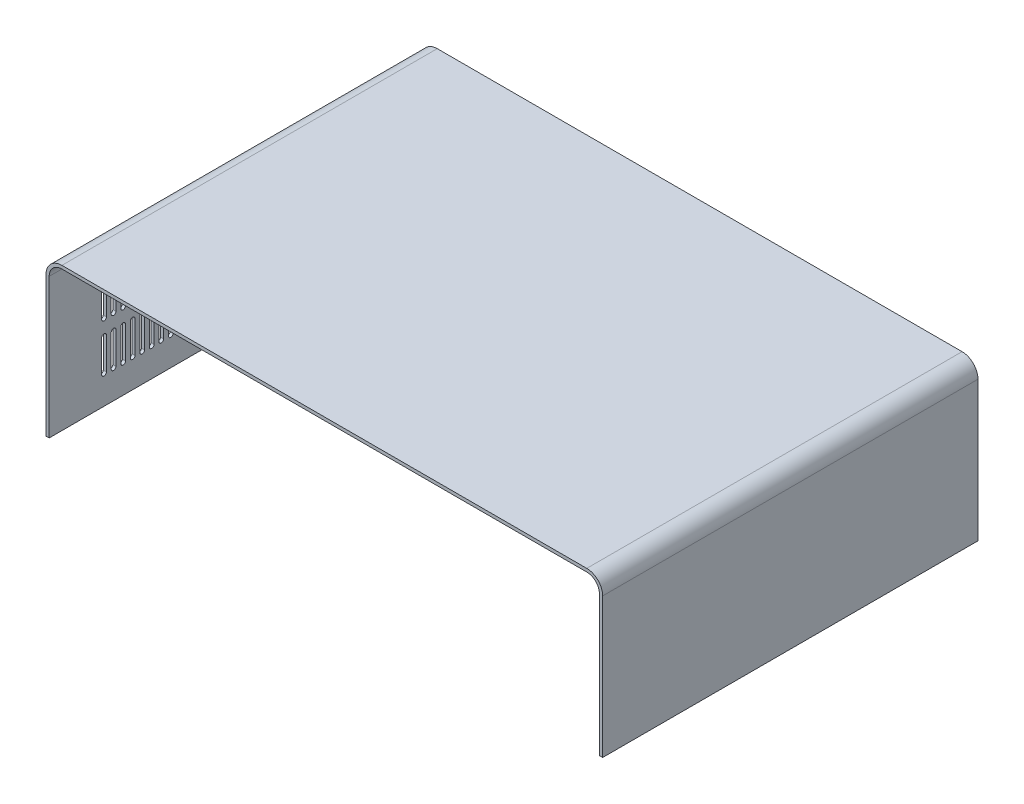
SolidWorks part; units mm, degrees
ref_plane "Front Plane" through (0, 0, 0) normal (0, 0, 1) x (1, 0, 0)
ref_plane "Top Plane" through (0, 0, 0) normal (0, 1, 0) x (1, 0, 0)
ref_plane "Right Plane" through (0, 0, 0) normal (1, 0, 0) x (0, 0, -1)
sketch "Sketch1" plane through (0, 0, 0) normal (0, 0, 1) x (1, 0, 0)
  line L0 (-87.5, 0) -> (-87.5, 44)
  line L1 (-82.5, 49) -> (82.5, 49)
  line L2 (87.5, 44) -> (87.5, 0)
  line L3 (-86.5, 0) -> (-86.5, 44)
  line L4 (-82.5, 48) -> (82.5, 48)
  line L5 (86.5, 44) -> (86.5, 0)
  line L6 (-87.5, 0) -> (-86.5, 0)
  line L7 (86.5, 0) -> (87.5, 0)
  arc A0 (-87.5, 44) -> (-82.5, 49) centre (-82.5, 44) cw
  arc A1 (82.5, 49) -> (87.5, 44) centre (82.5, 44) cw
  arc A2 (-86.5, 44) -> (-82.5, 48) centre (-82.5, 44) cw
  arc A3 (82.5, 48) -> (86.5, 44) centre (82.5, 44) cw
  point P16 (0, 49)
  dimension "D1" = 5
  dimension "D2" = 5
  dimension "D3" = 49
  dimension "D4" = 175
  dimension "D5" = 1
extrude "Extrude1" add sketch "Sketch1" against normal blind 118
sketch "Sketch2" plane through (-87.5, 0, 0) normal (-1, 0, 0) x (0, 0, 1)
  line L0 (-75, 34) -> (-75, 24)
  line L1 (-73.5, 34) -> (-73.5, 24)
  line L2 (0, 44) -> (0, 0) construction
  line L3 (-118, 49) -> (0, 49) construction
  line L4 (-72, 34) -> (-72, 24)
  line L5 (-70.5, 34) -> (-70.5, 24)
  line L6 (-69, 34) -> (-69, 24)
  line L7 (-67.5, 34) -> (-67.5, 24)
  line L8 (-66, 34) -> (-66, 24)
  line L9 (-64.5, 34) -> (-64.5, 24)
  line L10 (-63, 34) -> (-63, 24)
  line L11 (-61.5, 34) -> (-61.5, 24)
  line L12 (-60, 34) -> (-60, 24)
  line L13 (-58.5, 34) -> (-58.5, 24)
  line L14 (-57, 34) -> (-57, 24)
  line L15 (-55.5, 34) -> (-55.5, 24)
  line L16 (-54, 34) -> (-54, 24)
  line L17 (-52.5, 34) -> (-52.5, 24)
  line L18 (-51, 34) -> (-51, 24)
  line L19 (-49.5, 34) -> (-49.5, 24)
  line L20 (-48, 34) -> (-48, 24)
  line L21 (-46.5, 34) -> (-46.5, 24)
  line L22 (-45, 34) -> (-45, 24)
  line L23 (-43.5, 34) -> (-43.5, 24)
  line L24 (-42, 34) -> (-42, 24)
  line L25 (-40.5, 34) -> (-40.5, 24)
  line L26 (-39, 34) -> (-39, 24)
  line L27 (-37.5, 34) -> (-37.5, 24)
  line L28 (-36, 34) -> (-36, 24)
  line L29 (-34.5, 34) -> (-34.5, 24)
  line L30 (-33, 34) -> (-33, 24)
  line L31 (-31.5, 34) -> (-31.5, 24)
  line L32 (-30, 34) -> (-30, 24)
  line L33 (-28.5, 34) -> (-28.5, 24)
  line L34 (-27, 34) -> (-27, 24)
  line L35 (-25.5, 34) -> (-25.5, 24)
  line L36 (-24, 34) -> (-24, 24)
  line L37 (-22.5, 34) -> (-22.5, 24)
  line L38 (-21, 34) -> (-21, 24)
  line L39 (-19.5, 34) -> (-19.5, 24)
  line L40 (-18, 34) -> (-18, 24)
  line L41 (-16.5, 34) -> (-16.5, 24)
  line L42 (-75, 19) -> (-75, 9)
  line L43 (-73.5, 19) -> (-73.5, 9)
  line L44 (-72, 19) -> (-72, 9)
  line L45 (-70.5, 19) -> (-70.5, 9)
  line L46 (-69, 19) -> (-69, 9)
  line L47 (-67.5, 19) -> (-67.5, 9)
  line L48 (-66, 19) -> (-66, 9)
  line L49 (-64.5, 19) -> (-64.5, 9)
  line L50 (-63, 19) -> (-63, 9)
  line L51 (-61.5, 19) -> (-61.5, 9)
  line L52 (-60, 19) -> (-60, 9)
  line L53 (-58.5, 19) -> (-58.5, 9)
  line L54 (-57, 19) -> (-57, 9)
  line L55 (-55.5, 19) -> (-55.5, 9)
  line L56 (-54, 19) -> (-54, 9)
  line L57 (-52.5, 19) -> (-52.5, 9)
  line L58 (-51, 19) -> (-51, 9)
  line L59 (-49.5, 19) -> (-49.5, 9)
  line L60 (-48, 19) -> (-48, 9)
  line L61 (-46.5, 19) -> (-46.5, 9)
  line L62 (-45, 19) -> (-45, 9)
  line L63 (-43.5, 19) -> (-43.5, 9)
  line L64 (-42, 19) -> (-42, 9)
  line L65 (-40.5, 19) -> (-40.5, 9)
  line L66 (-39, 19) -> (-39, 9)
  line L67 (-37.5, 19) -> (-37.5, 9)
  line L68 (-36, 19) -> (-36, 9)
  line L69 (-34.5, 19) -> (-34.5, 9)
  line L70 (-33, 19) -> (-33, 9)
  line L71 (-31.5, 19) -> (-31.5, 9)
  line L72 (-30, 19) -> (-30, 9)
  line L73 (-28.5, 19) -> (-28.5, 9)
  line L74 (-27, 19) -> (-27, 9)
  line L75 (-25.5, 19) -> (-25.5, 9)
  line L76 (-24, 19) -> (-24, 9)
  line L77 (-22.5, 19) -> (-22.5, 9)
  line L78 (-21, 19) -> (-21, 9)
  line L79 (-19.5, 19) -> (-19.5, 9)
  line L80 (-18, 19) -> (-18, 9)
  line L81 (-16.5, 19) -> (-16.5, 9)
  arc A0 (-75, 34) -> (-73.5, 34) centre (-74.25, 34) cw
  arc A1 (-75, 24) -> (-73.5, 24) centre (-74.25, 24) ccw
  arc A2 (-72, 34) -> (-70.5, 34) centre (-71.25, 34) cw
  arc A3 (-72, 24) -> (-70.5, 24) centre (-71.25, 24) ccw
  arc A4 (-69, 34) -> (-67.5, 34) centre (-68.25, 34) cw
  arc A5 (-69, 24) -> (-67.5, 24) centre (-68.25, 24) ccw
  arc A6 (-66, 34) -> (-64.5, 34) centre (-65.25, 34) cw
  arc A7 (-66, 24) -> (-64.5, 24) centre (-65.25, 24) ccw
  arc A8 (-63, 34) -> (-61.5, 34) centre (-62.25, 34) cw
  arc A9 (-63, 24) -> (-61.5, 24) centre (-62.25, 24) ccw
  arc A10 (-60, 34) -> (-58.5, 34) centre (-59.25, 34) cw
  arc A11 (-60, 24) -> (-58.5, 24) centre (-59.25, 24) ccw
  arc A12 (-57, 34) -> (-55.5, 34) centre (-56.25, 34) cw
  arc A13 (-57, 24) -> (-55.5, 24) centre (-56.25, 24) ccw
  arc A14 (-54, 34) -> (-52.5, 34) centre (-53.25, 34) cw
  arc A15 (-54, 24) -> (-52.5, 24) centre (-53.25, 24) ccw
  arc A16 (-51, 34) -> (-49.5, 34) centre (-50.25, 34) cw
  arc A17 (-51, 24) -> (-49.5, 24) centre (-50.25, 24) ccw
  arc A18 (-48, 34) -> (-46.5, 34) centre (-47.25, 34) cw
  arc A19 (-48, 24) -> (-46.5, 24) centre (-47.25, 24) ccw
  arc A20 (-45, 34) -> (-43.5, 34) centre (-44.25, 34) cw
  arc A21 (-45, 24) -> (-43.5, 24) centre (-44.25, 24) ccw
  arc A22 (-42, 34) -> (-40.5, 34) centre (-41.25, 34) cw
  arc A23 (-42, 24) -> (-40.5, 24) centre (-41.25, 24) ccw
  arc A24 (-39, 34) -> (-37.5, 34) centre (-38.25, 34) cw
  arc A25 (-39, 24) -> (-37.5, 24) centre (-38.25, 24) ccw
  arc A26 (-36, 34) -> (-34.5, 34) centre (-35.25, 34) cw
  arc A27 (-36, 24) -> (-34.5, 24) centre (-35.25, 24) ccw
  arc A28 (-33, 34) -> (-31.5, 34) centre (-32.25, 34) cw
  arc A29 (-33, 24) -> (-31.5, 24) centre (-32.25, 24) ccw
  arc A30 (-30, 34) -> (-28.5, 34) centre (-29.25, 34) cw
  arc A31 (-30, 24) -> (-28.5, 24) centre (-29.25, 24) ccw
  arc A32 (-27, 34) -> (-25.5, 34) centre (-26.25, 34) cw
  arc A33 (-27, 24) -> (-25.5, 24) centre (-26.25, 24) ccw
  arc A34 (-24, 34) -> (-22.5, 34) centre (-23.25, 34) cw
  arc A35 (-24, 24) -> (-22.5, 24) centre (-23.25, 24) ccw
  arc A36 (-21, 34) -> (-19.5, 34) centre (-20.25, 34) cw
  arc A37 (-21, 24) -> (-19.5, 24) centre (-20.25, 24) ccw
  arc A38 (-18, 34) -> (-16.5, 34) centre (-17.25, 34) cw
  arc A39 (-18, 24) -> (-16.5, 24) centre (-17.25, 24) ccw
  arc A40 (-75, 19) -> (-73.5, 19) centre (-74.25, 19) cw
  arc A41 (-75, 9) -> (-73.5, 9) centre (-74.25, 9) ccw
  arc A42 (-72, 19) -> (-70.5, 19) centre (-71.25, 19) cw
  arc A43 (-72, 9) -> (-70.5, 9) centre (-71.25, 9) ccw
  arc A44 (-69, 19) -> (-67.5, 19) centre (-68.25, 19) cw
  arc A45 (-69, 9) -> (-67.5, 9) centre (-68.25, 9) ccw
  arc A46 (-66, 19) -> (-64.5, 19) centre (-65.25, 19) cw
  arc A47 (-66, 9) -> (-64.5, 9) centre (-65.25, 9) ccw
  arc A48 (-63, 19) -> (-61.5, 19) centre (-62.25, 19) cw
  arc A49 (-63, 9) -> (-61.5, 9) centre (-62.25, 9) ccw
  arc A50 (-60, 19) -> (-58.5, 19) centre (-59.25, 19) cw
  arc A51 (-60, 9) -> (-58.5, 9) centre (-59.25, 9) ccw
  arc A52 (-57, 19) -> (-55.5, 19) centre (-56.25, 19) cw
  arc A53 (-57, 9) -> (-55.5, 9) centre (-56.25, 9) ccw
  arc A54 (-54, 19) -> (-52.5, 19) centre (-53.25, 19) cw
  arc A55 (-54, 9) -> (-52.5, 9) centre (-53.25, 9) ccw
  arc A56 (-51, 19) -> (-49.5, 19) centre (-50.25, 19) cw
  arc A57 (-51, 9) -> (-49.5, 9) centre (-50.25, 9) ccw
  arc A58 (-48, 19) -> (-46.5, 19) centre (-47.25, 19) cw
  arc A59 (-48, 9) -> (-46.5, 9) centre (-47.25, 9) ccw
  arc A60 (-45, 19) -> (-43.5, 19) centre (-44.25, 19) cw
  arc A61 (-45, 9) -> (-43.5, 9) centre (-44.25, 9) ccw
  arc A62 (-42, 19) -> (-40.5, 19) centre (-41.25, 19) cw
  arc A63 (-42, 9) -> (-40.5, 9) centre (-41.25, 9) ccw
  arc A64 (-39, 19) -> (-37.5, 19) centre (-38.25, 19) cw
  arc A65 (-39, 9) -> (-37.5, 9) centre (-38.25, 9) ccw
  arc A66 (-36, 19) -> (-34.5, 19) centre (-35.25, 19) cw
  arc A67 (-36, 9) -> (-34.5, 9) centre (-35.25, 9) ccw
  arc A68 (-33, 19) -> (-31.5, 19) centre (-32.25, 19) cw
  arc A69 (-33, 9) -> (-31.5, 9) centre (-32.25, 9) ccw
  arc A70 (-30, 19) -> (-28.5, 19) centre (-29.25, 19) cw
  arc A71 (-30, 9) -> (-28.5, 9) centre (-29.25, 9) ccw
  arc A72 (-27, 19) -> (-25.5, 19) centre (-26.25, 19) cw
  arc A73 (-27, 9) -> (-25.5, 9) centre (-26.25, 9) ccw
  arc A74 (-24, 19) -> (-22.5, 19) centre (-23.25, 19) cw
  arc A75 (-24, 9) -> (-22.5, 9) centre (-23.25, 9) ccw
  arc A76 (-21, 19) -> (-19.5, 19) centre (-20.25, 19) cw
  arc A77 (-21, 9) -> (-19.5, 9) centre (-20.25, 9) ccw
  arc A78 (-18, 19) -> (-16.5, 19) centre (-17.25, 19) cw
  arc A79 (-18, 9) -> (-16.5, 9) centre (-17.25, 9) ccw
  dimension "D1" = 1.5
  dimension "D2" = 10
  dimension "D3" = 75
  dimension "D4" = 15
extrude "Extrude2" cut sketch "Sketch2" against normal up to next (1 mm away)
